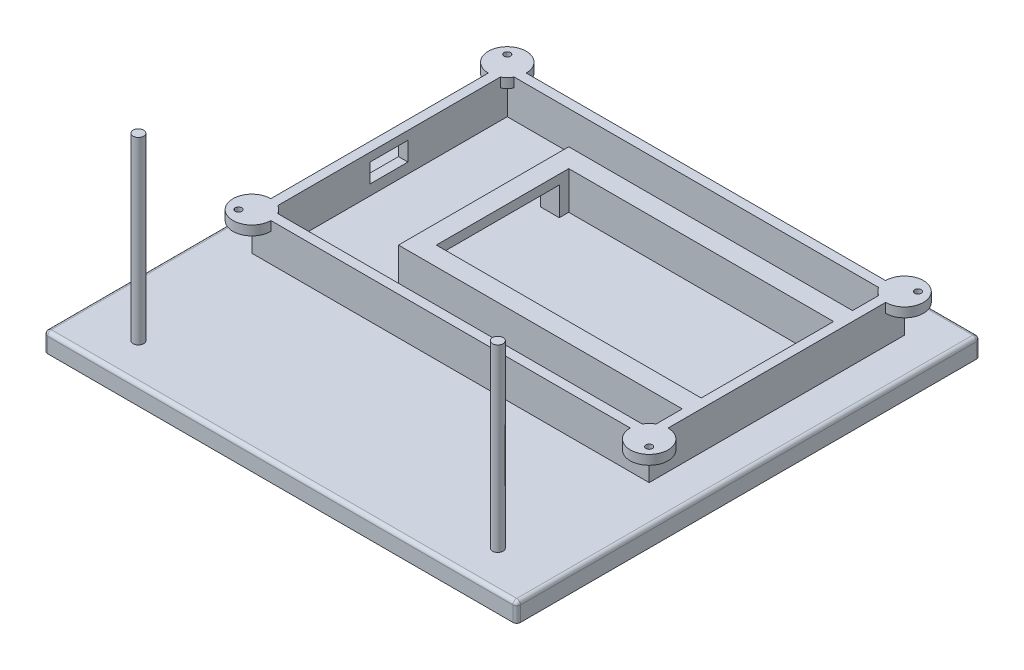
SolidWorks part; units mm, degrees
ref_plane "Front Plane" through (0, 0, 0) normal (0, 0, 1) x (1, 0, 0)
ref_plane "Top Plane" through (0, 0, 0) normal (0, 1, 0) x (1, 0, 0)
ref_plane "Right Plane" through (0, 0, 0) normal (1, 0, 0) x (0, 0, -1)
sketch "Sketch1" plane through (0, 0, 0) normal (0, 1, 0) x (1, 0, 0)
  line L0 (0, 0) -> (210, 0)
  line L1 (210, 0) -> (210, -135)
  line L2 (210, -135) -> (0, -135)
  line L3 (0, -135) -> (0, 0)
  line L4 (0, 0) -> (5, 0)
  line L5 (5, 0) -> (5, -130)
  line L6 (5, -130) -> (205, -130)
  line L7 (205, -130) -> (205, -5)
  line L8 (205, -5) -> (5, -5)
extrude "Boss-Extrude3" add sketch "Sketch1" along normal blind 40
sketch "Sketch3" plane through (0, 0, 0) normal (0, -1, 0) x (-1, 0, 0)
  line L0 (0, -135) -> (0, -145)
  line L1 (0, -145) -> (-220, -145)
  line L2 (-220, -145) -> (-220, 10)
  line L3 (-220, 10) -> (10, 10)
  line L4 (10, 10) -> (10, -145)
  line L5 (10, -145) -> (0, -145)
extrude "Boss-Extrude4" add sketch "Sketch3" along normal blind 10
sketch "Sketch4" plane through (0, 0, 0) normal (0, 1, 0) x (1, 0, 0)
  line L0 (205, -67.5) -> (205, -32.5)
  line L1 (205, -130) -> (205, -5) construction
  line L2 (205, -32.5) -> (65, -32.5)
  line L3 (65, -32.5) -> (65, -102.5)
  line L4 (65, -102.5) -> (205, -102.5)
  line L5 (205, -102.5) -> (205, -67.5)
  line L6 (205, -32.5) -> (205, -27.5)
  line L7 (205, -130) -> (205, -5) construction
  line L8 (205, -27.5) -> (60, -27.5)
  line L9 (60, -27.5) -> (60, -107.5)
  line L10 (60, -107.5) -> (205, -107.5)
  line L11 (205, -107.5) -> (205, -102.5)
extrude "Extrude-Thin1" add sketch "Sketch4" along normal blind 40 thin contours L2 L3 L4
sketch "Sketch5" plane through (55, 0, 0) normal (-1, 0, 0) x (0, 0, 1)
  line L0 (67.5, 0) -> (67.5, 15)
  line L1 (-10, 0) -> (145, 0) construction
  line L2 (67.5, 15) -> (97.5, 15)
  line L3 (97.5, 15) -> (97.5, 0)
  line L4 (135, 0) -> (0, 0) construction
  line L5 (97.5, 0) -> (37.5, 0)
  line L6 (37.5, 0) -> (37.5, 15)
  line L7 (37.5, 15) -> (67.5, 15)
extrude "Cut-Extrude2" cut sketch "Sketch5" against normal blind 40 contours L3 L2 L0 L1 | L7 L6 L1 L0
sketch "Sketch6" plane through (0, 40, 0) normal (0, 1, 0) x (1, 0, 0)
  line L0 (0, 0) -> (210, 0)
  line L1 (210, 0) -> (210, -135) construction
  line L2 (0, 0) -> (210, 0) construction
  line L3 (210, 0) -> (210, -135)
  line L4 (210, -135) -> (0, -135)
  line L5 (0, -135) -> (0, 0)
extrude "Cut-Extrude3" cut sketch "Sketch6" against normal blind 20
sketch "Sketch7" plane through (0, 20, 0) normal (0, 1, 0) x (1, 0, 0)
  circle A0 centre (0, 0) radius 10
  circle A1 centre (210, 0) radius 10
  circle A2 centre (210, -135) radius 10
  circle A3 centre (0, -135) radius 10
extrude "Boss-Extrude5" add sketch "Sketch7" against normal blind 5
sketch "Sketch8" plane through (0, 20, 0) normal (0, 1, 0) x (1, 0, 0)
  line L0 (0, 0) -> (-7.0711, 7.0711)
  line L1 (217.0711, 7.0711) -> (210, 0)
  line L2 (217.0711, -142.0711) -> (210, -135)
  line L3 (-7.0711, -142.0711) -> (0, -135)
  arc A0 (10, 0) -> (0, -10) centre (0, 0) ccw construction
  arc A1 (210, -10) -> (200, 0) centre (210, 0) ccw construction
  arc A2 (200, -135) -> (210, -125) centre (210, -135) ccw construction
  arc A3 (0, -125) -> (10, -135) centre (0, -135) ccw construction
  circle A4 centre (-3.5355, 3.5355) radius 1.7
  circle A5 centre (213.5355, 3.5355) radius 1.7
  circle A6 centre (213.5355, -138.5355) radius 1.7
  circle A7 centre (-3.5355, -138.5355) radius 1.7
extrude "Cut-Extrude5" cut sketch "Sketch8" against normal blind 5 contours A6 | A5 | A4 | A7
sketch "Sketch9" plane through (0, 0, 0) normal (-1, 0, 0) x (0, 0, 1)
  line L0 (67.5, 0) -> (67.5, 10.5)
  line L1 (135, 0) -> (0, 0) construction
  line L2 (67.5, 10.5) -> (77.5, 10.5)
  line L3 (77.5, 10.5) -> (77.5, 5.5)
  line L4 (77.5, 5.5) -> (57.5, 5.5)
  line L5 (57.5, 5.5) -> (57.5, 10.5)
  line L6 (57.5, 10.5) -> (67.5, 10.5)
  line L7 (57.5, 10.5) -> (57.5, 15.5)
  line L8 (57.5, 15.5) -> (77.5, 15.5)
  line L9 (77.5, 15.5) -> (77.5, 10.5)
  line L10 (77.5, 15.5) -> (77.5, 10.5)
extrude "Cut-Extrude6" cut sketch "Sketch9" against normal blind 10 contours L9 L8 L7 L6 L2 | L4 L3 L2 L0 | L6 L5 L4 L0
sketch "Sketch10" plane through (0, 0, 0) normal (0, 1, 0) x (1, 0, 0)
  line L0 (-10, 10) -> (-10, 20)
  line L1 (-10, 20) -> (230, 20)
  line L2 (230, 20) -> (230, -225)
  line L3 (230, -225) -> (-20, -225)
  line L4 (-20, -225) -> (-20, 20)
  line L5 (-20, 20) -> (-10, 20)
  line L6 (-10, 10) -> (220, 10)
  line L7 (220, 10) -> (220, -145)
  line L8 (220, -145) -> (-10, -145)
  line L9 (-10, -145) -> (-10, 10)
extrude "Boss-Extrude6" add sketch "Sketch10" against normal blind 10
sketch "Sketch13" plane through (0, 0, 0) normal (-1, 0, 0) x (0, 0, 1)
  line L0 (135, 0) -> (205, 0)
  line L1 (225, 0) -> (-20, 0) construction
sketch "Sketch14" plane through (0, 0, 0) normal (0, 1, 0) x (1, 0, 0)
  line L0 (0, -205) -> (10, -205)
  line L1 (0, -135) -> (0, -205) construction
  line L2 (230, -205) -> (200, -205)
  line L3 (230, 20) -> (230, -225) construction
  circle A0 centre (10, -205) radius 2.8
  circle A1 centre (200, -205) radius 2.8
extrude "Boss-Extrude7" add sketch "Sketch14" along normal blind 95
fillet "Fillet1" radius 2 8 edges at (-20, -5, -20) (-20, -5, 225) (230, -5, 225) (230, -5, -20) (105, 0, -20) (230, 0, 102.5) (-20, 0, 102.5) (105, 0, 225)
